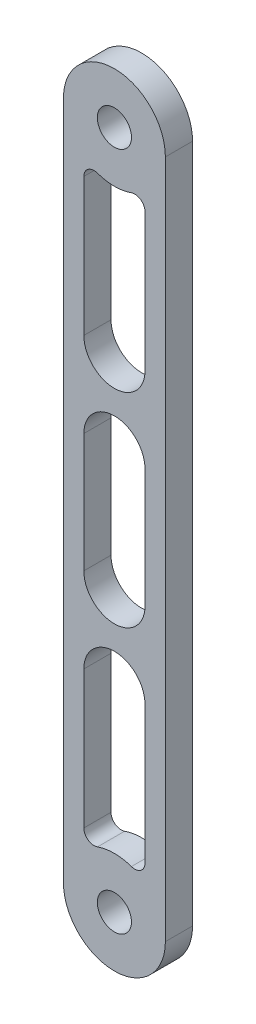
SolidWorks part; units mm, degrees
material "6061 合金"
ref_plane "前视基准面" through (0, 0, 0) normal (0, 0, 1) x (1, 0, 0)
ref_plane "上视基准面" through (0, 0, 0) normal (0, 1, 0) x (1, 0, 0)
ref_plane "右视基准面" through (0, 0, 0) normal (1, 0, 0) x (0, 0, -1)
other "Configuration Table"
sketch "草图1" plane through (0, 0, 0) normal (0, 0, 1) x (1, 0, 0)
  line L0 (-15, 0) -> (-15, -200)
  line L1 (15, 0) -> (15, -200)
  line L2 (-9, -16.9706) -> (-9, -57.5)
  line L3 (0, 0) -> (0, -200) construction
  line L4 (9, -16.9706) -> (9, -57.5)
  line L5 (0, -82.5) -> (0, -117.5) construction
  line L6 (9, -82.5) -> (9, -117.5)
  line L7 (-9, -82.5) -> (-9, -117.5)
  line L8 (15, -100) -> (-15, -100) construction
  line L11 (-9, -183.0294) -> (-9, -142.5)
  line L12 (9, -183.0294) -> (9, -142.5)
  circle A0 centre (0, 0) radius 5.025
  arc A1 (15, 0) -> (-15, 0) centre (0, 0) ccw
  circle A2 centre (0, -200) radius 5.025
  arc A3 (-15, -200) -> (15, -200) centre (0, -200) ccw
  arc A4 (-5, -14.1421) -> (5, -14.1421) centre (0, 0) ccw
  arc A5 (-9, -57.5) -> (9, -57.5) centre (0, -57.5) ccw
  arc A6 (9, -16.9706) -> (5, -14.1421) centre (6, -16.9706) ccw
  arc A7 (-5, -14.1421) -> (-9, -16.9706) centre (-6, -16.9706) ccw
  arc A8 (9, -82.5) -> (-9, -82.5) centre (0, -82.5) ccw
  arc A9 (-9, -117.5) -> (9, -117.5) centre (0, -117.5) ccw
  arc A12 (-5, -185.8579) -> (-9, -183.0294) centre (-6, -183.0294) cw
  arc A13 (-5, -185.8579) -> (5, -185.8579) centre (0, -200) cw
  arc A14 (9, -183.0294) -> (5, -185.8579) centre (6, -183.0294) cw
  arc A15 (-9, -142.5) -> (9, -142.5) centre (0, -142.5) cw
  point P16 (9, -12)
  point P19 (-9, -12)
  point P22 (0, -100)
  dimension "D1" = 10.05
  dimension "D2" = 200
  dimension "D3" = 30
  dimension "D4" = 10.05
  dimension "D6" = 3
  dimension "D7" = 15
  dimension "D10" = 25
  dimension "D5" = 6
  dimension "D8" = 6
  dimension "D12" = 35
extrude "凸台-拉伸1" add sketch "草图1" along normal blind 8
